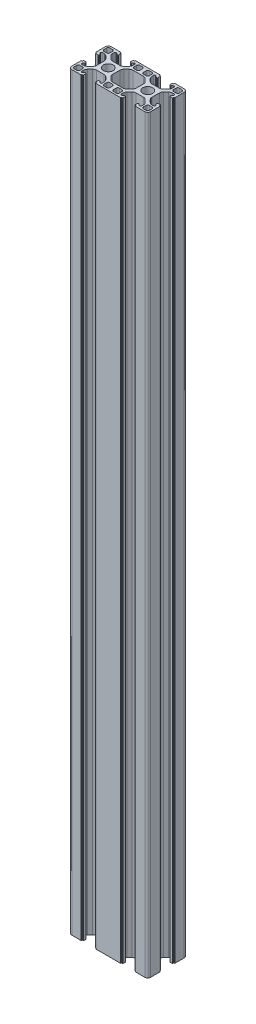
SolidWorks part; units mm, degrees
ref_plane "Спереди" through (0, 0, 0) normal (0, 0, 1) x (1, 0, 0)
ref_plane "Сверху" through (0, 0, 0) normal (0, 1, 0) x (1, 0, 0)
ref_plane "Справа" through (0, 0, 0) normal (1, 0, 0) x (0, 0, -1)
sketch "Эскиз1" plane through (0, 0, 0) normal (0, 1, 0) x (1, 0, 0)
  line L0 (-3.1522, 8.2837) -> (-1.6522, 6.7837) construction
  line L1 (18.3478, 9.7837) -> (15.3478, 6.7837) construction
  line L2 (-10.7522, 0.6837) -> (-0.7522, 10.6837) construction
  line L3 (9.2478, 4.6837) -> (11.1466, 4.6837)
  line L4 (9.2478, 0.6837) -> (19.2478, 10.6837) construction
  line L5 (16.8478, 8.2837) -> (15.3478, 9.7837) construction
  line L6 (12.5608, 5.2695) -> (13.862, 6.5707)
  line L7 (16.1478, 6.7837) -> (17.5478, 6.7837)
  line L8 (15.3478, 7.5837) -> (15.3478, 8.9837)
  line L9 (17.5478, 9.7837) -> (16.1478, 9.7837)
  line L10 (14.4478, 8.8837) -> (14.4478, 7.9849)
  line L11 (13.011, 8.757) -> (13.4914, 9.2373)
  line L12 (12.4478, 10.2328) -> (12.9478, 10.2328)
  line L13 (12.8343, 8.6837) -> (12.5478, 8.6837)
  line L14 (13.8449, 9.3837) -> (13.9478, 9.3837)
  line L15 (12.9478, 10.5337) -> (12.9478, 10.2328)
  line L16 (12.2978, 10.0828) -> (12.2978, 8.9337)
  line L17 (17.7478, 10.6837) -> (13.0978, 10.6837)
  line L18 (18.3478, 8.9837) -> (18.3478, 7.5837)
  line L19 (19.2478, 9.1837) -> (19.2478, 4.5337)
  line L20 (18.6469, 3.7337) -> (17.4978, 3.7337)
  line L21 (19.0978, 4.3837) -> (18.7969, 4.3837)
  line L22 (17.9478, 5.2808) -> (17.9478, 5.3837)
  line L23 (17.2478, 4.2702) -> (17.2478, 3.9837)
  line L24 (18.7969, 3.8837) -> (18.7969, 4.3837)
  line L25 (17.321, 4.447) -> (17.8014, 4.9273)
  line L26 (17.4478, 5.8837) -> (16.549, 5.8837)
  line L27 (13.8336, 3.9967) -> (15.1348, 5.2979)
  line L28 (13.2478, 0.6837) -> (13.2478, 2.5825)
  line L29 (13.2478, 0.6837) -> (13.2478, -1.2151)
  line L30 (13.8336, -2.6293) -> (15.1348, -3.9305)
  line L31 (15.3478, -6.2163) -> (15.3478, -7.6163)
  line L32 (16.1478, -5.4163) -> (17.5478, -5.4163)
  line L33 (18.3478, -7.6163) -> (18.3478, -6.2163)
  line L34 (17.4478, -4.5163) -> (16.549, -4.5163)
  line L35 (17.321, -3.0795) -> (17.8014, -3.5598)
  line L36 (18.7969, -2.5163) -> (18.7969, -3.0163)
  line L37 (17.2478, -2.9027) -> (17.2478, -2.6163)
  line L38 (17.9478, -3.9134) -> (17.9478, -4.0163)
  line L39 (19.0978, -3.0163) -> (18.7969, -3.0163)
  line L40 (18.6469, -2.3663) -> (17.4978, -2.3663)
  line L41 (19.2478, -7.8163) -> (19.2478, -3.1663)
  line L42 (17.5478, -8.4163) -> (16.1478, -8.4163)
  line L43 (17.7478, -9.3163) -> (13.0978, -9.3163)
  line L44 (12.2978, -8.7153) -> (12.2978, -7.5663)
  line L45 (12.9478, -9.1663) -> (12.9478, -8.8653)
  line L46 (13.8449, -8.0163) -> (13.9478, -8.0163)
  line L47 (12.8343, -7.3163) -> (12.5478, -7.3163)
  line L48 (12.4478, -8.8653) -> (12.9478, -8.8653)
  line L49 (13.011, -7.3895) -> (13.4914, -7.8698)
  line L50 (14.4478, -7.5163) -> (14.4478, -6.6175)
  line L51 (12.5608, -3.9021) -> (13.862, -5.2033)
  line L52 (9.2478, -3.3163) -> (11.1466, -3.3163)
  line L53 (18.3478, -8.4163) -> (15.3478, -5.4163) construction
  line L54 (9.2478, 0.6837) -> (19.2478, -9.3163) construction
  line L55 (16.8478, -6.9163) -> (18.3478, -5.4163) construction
  line L56 (9.2478, -3.3163) -> (7.349, -3.3163)
  line L57 (5.9348, -3.9021) -> (4.6336, -5.2033)
  line L58 (2.3478, -5.4163) -> (0.9478, -5.4163)
  line L59 (3.1478, -6.2163) -> (3.1478, -7.6163)
  line L60 (0.9478, -8.4163) -> (2.3478, -8.4163)
  line L61 (4.0478, -7.5163) -> (4.0478, -6.6175)
  line L62 (5.4846, -7.3895) -> (5.0043, -7.8698)
  line L63 (6.0478, -8.8653) -> (5.5478, -8.8653)
  line L64 (5.6614, -7.3163) -> (5.9478, -7.3163)
  line L65 (4.6507, -8.0163) -> (4.5478, -8.0163)
  line L66 (5.5478, -9.1663) -> (5.5478, -8.8653)
  line L67 (6.1978, -8.7153) -> (6.1978, -7.5663)
  line L68 (0.7478, -9.3163) -> (5.3978, -9.3163)
  line L69 (0.1478, -7.6163) -> (0.1478, -6.2163)
  line L70 (1.0478, -4.5163) -> (1.9466, -4.5163)
  line L71 (4.662, -2.6293) -> (3.3608, -3.9305)
  line L72 (5.2478, 0.6837) -> (5.2478, -1.2151)
  line L73 (-1.6522, 9.7837) -> (-4.6522, 6.7837) construction
  line L74 (0.1478, -8.4163) -> (3.1478, -5.4163) construction
  line L75 (-3.1522, -6.9163) -> (-4.6522, -8.4163) construction
  line L76 (9.2478, 0.6837) -> (-0.7522, -9.3163) construction
  line L77 (1.6478, -6.9163) -> (3.1478, -8.4163) construction
  line L78 (5.2478, 0.6837) -> (5.2478, 2.5825)
  line L79 (4.662, 3.9967) -> (3.3608, 5.2979)
  line L80 (3.1478, 7.5837) -> (3.1478, 8.9837)
  line L81 (2.3478, 6.7837) -> (0.9478, 6.7837)
  line L82 (0.1478, 8.9837) -> (0.1478, 7.5837)
  line L83 (1.0478, 5.8837) -> (1.9466, 5.8837)
  line L84 (0.9478, 9.7837) -> (2.3478, 9.7837)
  line L85 (0.7478, 10.6837) -> (5.3978, 10.6837)
  line L86 (6.1978, 10.0828) -> (6.1978, 8.9337)
  line L87 (5.5478, 10.5337) -> (5.5478, 10.2328)
  line L88 (4.6507, 9.3837) -> (4.5478, 9.3837)
  line L89 (5.6614, 8.6837) -> (5.9478, 8.6837)
  line L90 (6.0478, 10.2328) -> (5.5478, 10.2328)
  line L91 (5.4846, 8.757) -> (5.0043, 9.2373)
  line L92 (4.0478, 8.8837) -> (4.0478, 7.9849)
  line L93 (5.9348, 5.2695) -> (4.6336, 6.5707)
  line L94 (9.2478, 4.6837) -> (7.349, 4.6837)
  line L95 (-2.5162, 0.6837) -> (20.7522, 0.6837) construction
  line L96 (0.1478, 9.7837) -> (3.1478, 6.7837) construction
  line L97 (9.2478, -11.4027) -> (9.2478, 11.4027) construction
  line L98 (9.2478, 0.6837) -> (-0.7522, 10.6837) construction
  line L99 (1.6478, 8.2837) -> (0.1478, 6.7837) construction
  line L100 (-10.7522, 0.6837) -> (-0.7522, -9.3163) construction
  line L101 (-1.6522, -8.4163) -> (-4.6522, -5.4163) construction
  line L102 (-18.3522, -6.9163) -> (-19.8522, -5.4163) construction
  line L103 (-10.7522, 0.6837) -> (-20.7522, -9.3163) construction
  line L104 (-19.8522, -8.4163) -> (-16.8522, -5.4163) construction
  line L105 (-18.3522, 8.2837) -> (-16.8522, 9.7837) construction
  line L106 (-10.7522, 0.6837) -> (-20.7522, 10.6837) construction
  line L107 (-19.8522, 9.7837) -> (-16.8522, 6.7837) construction
  line L108 (-10.7522, 4.6837) -> (-8.8534, 4.6837)
  line L109 (-7.4392, 5.2695) -> (-6.138, 6.5707)
  line L110 (-5.5522, 8.8837) -> (-5.5522, 7.9849)
  line L111 (-6.989, 8.757) -> (-6.5086, 9.2373)
  line L112 (-7.5522, 10.2328) -> (-7.0522, 10.2328)
  line L113 (-7.1657, 8.6837) -> (-7.4522, 8.6837)
  line L114 (-6.1551, 9.3837) -> (-6.0522, 9.3837)
  line L115 (-7.0522, 10.5337) -> (-7.0522, 10.2328)
  line L116 (-7.7022, 10.0828) -> (-7.7022, 8.9337)
  line L117 (-2.2522, 10.6837) -> (-6.9022, 10.6837)
  line L118 (-2.4522, 9.7837) -> (-3.8522, 9.7837)
  line L119 (-2.5522, 5.8837) -> (-3.451, 5.8837)
  line L120 (-1.6522, 8.9837) -> (-1.6522, 7.5837)
  line L121 (-3.8522, 6.7837) -> (-2.4522, 6.7837)
  line L122 (-4.6522, 7.5837) -> (-4.6522, 8.9837)
  line L123 (-6.1664, 3.9967) -> (-4.8652, 5.2979)
  line L124 (-6.7522, 0.6837) -> (-6.7522, 2.5825)
  line L125 (-6.7522, 0.6837) -> (-6.7522, -1.2151)
  line L126 (-6.1664, -2.6293) -> (-4.8652, -3.9305)
  line L127 (-2.5522, -4.5163) -> (-3.451, -4.5163)
  line L128 (-1.6522, -7.6163) -> (-1.6522, -6.2163)
  line L129 (-2.2522, -9.3163) -> (-6.9022, -9.3163)
  line L130 (-7.7022, -8.7153) -> (-7.7022, -7.5663)
  line L131 (-7.0522, -9.1663) -> (-7.0522, -8.8653)
  line L132 (-6.1551, -8.0163) -> (-6.0522, -8.0163)
  line L133 (-7.1657, -7.3163) -> (-7.4522, -7.3163)
  line L134 (-7.5522, -8.8653) -> (-7.0522, -8.8653)
  line L135 (-6.989, -7.3895) -> (-6.5086, -7.8698)
  line L136 (-5.5522, -7.5163) -> (-5.5522, -6.6175)
  line L137 (-2.4522, -8.4163) -> (-3.8522, -8.4163)
  line L138 (-4.6522, -6.2163) -> (-4.6522, -7.6163)
  line L139 (-3.8522, -5.4163) -> (-2.4522, -5.4163)
  line L140 (-7.4392, -3.9021) -> (-6.138, -5.2033)
  line L141 (-10.7522, -3.3163) -> (-8.8534, -3.3163)
  line L142 (-10.7522, -3.3163) -> (-12.651, -3.3163)
  line L143 (-14.0652, -3.9021) -> (-15.3664, -5.2033)
  line L144 (-15.9522, -7.5163) -> (-15.9522, -6.6175)
  line L145 (-14.5154, -7.3895) -> (-14.9957, -7.8698)
  line L146 (-13.9522, -8.8653) -> (-14.4522, -8.8653)
  line L147 (-14.3386, -7.3163) -> (-14.0522, -7.3163)
  line L148 (-15.3493, -8.0163) -> (-15.4522, -8.0163)
  line L149 (-14.4522, -9.1663) -> (-14.4522, -8.8653)
  line L150 (-13.8022, -8.7153) -> (-13.8022, -7.5663)
  line L151 (-19.2522, -9.3163) -> (-14.6022, -9.3163)
  line L152 (-19.0522, -8.4163) -> (-17.6522, -8.4163)
  line L153 (-20.7522, -7.8163) -> (-20.7522, -3.1663)
  line L154 (-20.1512, -2.3663) -> (-19.0022, -2.3663)
  line L155 (-20.6022, -3.0163) -> (-20.3012, -3.0163)
  line L156 (-19.4522, -3.9134) -> (-19.4522, -4.0163)
  line L157 (-18.7522, -2.9027) -> (-18.7522, -2.6163)
  line L158 (-20.3012, -2.5163) -> (-20.3012, -3.0163)
  line L159 (-18.8254, -3.0795) -> (-19.3057, -3.5598)
  line L160 (-18.9522, -4.5163) -> (-18.0534, -4.5163)
  line L161 (-19.8522, -7.6163) -> (-19.8522, -6.2163)
  line L162 (-17.6522, -5.4163) -> (-19.0522, -5.4163)
  line L163 (-16.8522, -6.2163) -> (-16.8522, -7.6163)
  line L164 (-15.338, -2.6293) -> (-16.6392, -3.9305)
  line L165 (-14.7522, 0.6837) -> (-14.7522, -1.2151)
  line L166 (-14.7522, 0.6837) -> (-14.7522, 2.5825)
  line L167 (-15.338, 3.9967) -> (-16.6392, 5.2979)
  line L168 (-18.9522, 5.8837) -> (-18.0534, 5.8837)
  line L169 (-18.8254, 4.447) -> (-19.3057, 4.9273)
  line L170 (-20.3012, 3.8837) -> (-20.3012, 4.3837)
  line L171 (-18.7522, 4.2702) -> (-18.7522, 3.9837)
  line L172 (-19.4522, 5.2808) -> (-19.4522, 5.3837)
  line L173 (-20.6022, 4.3837) -> (-20.3012, 4.3837)
  line L174 (-20.1512, 3.7337) -> (-19.0022, 3.7337)
  line L175 (-20.7522, 9.1837) -> (-20.7522, 4.5337)
  line L176 (-19.8522, 8.9837) -> (-19.8522, 7.5837)
  line L177 (-19.2522, 10.6837) -> (-14.6022, 10.6837)
  line L178 (-13.8022, 10.0828) -> (-13.8022, 8.9337)
  line L179 (-14.4522, 10.5337) -> (-14.4522, 10.2328)
  line L180 (-15.3493, 9.3837) -> (-15.4522, 9.3837)
  line L181 (-14.3386, 8.6837) -> (-14.0522, 8.6837)
  line L182 (-13.9522, 10.2328) -> (-14.4522, 10.2328)
  line L183 (-14.5154, 8.757) -> (-14.9957, 9.2373)
  line L184 (-15.9522, 8.8837) -> (-15.9522, 7.9849)
  line L185 (-19.0522, 9.7837) -> (-17.6522, 9.7837)
  line L186 (-16.8522, 7.5837) -> (-16.8522, 8.9837)
  line L187 (-17.6522, 6.7837) -> (-19.0522, 6.7837)
  line L188 (-14.0652, 5.2695) -> (-15.3664, 6.5707)
  line L189 (-10.7522, 4.6837) -> (-12.651, 4.6837)
  line L190 (-2.2522, -9.3163) -> (0.7478, -9.3163)
  line L191 (-2.5522, -4.5163) -> (1.0478, -4.5163)
  line L192 (-2.5522, 5.8837) -> (1.0478, 5.8837)
  line L193 (-2.2522, 10.6837) -> (0.7478, 10.6837)
  arc A0 (18.3478, 8.9837) -> (17.5478, 9.7837) centre (17.5478, 8.9837) ccw
  arc A1 (16.1478, 9.7837) -> (15.3478, 8.9837) centre (16.1478, 8.9837) ccw
  arc A2 (16.1478, 6.7837) -> (15.3478, 7.5837) centre (16.1478, 7.5837) cw
  arc A3 (17.7478, 10.6837) -> (19.2478, 9.1837) centre (17.7478, 9.1837) cw
  arc A4 (12.4478, 10.2328) -> (12.2978, 10.0828) centre (12.4478, 10.0828) ccw
  arc A5 (13.0978, 10.6837) -> (12.9478, 10.5337) centre (13.0978, 10.5337) ccw
  arc A6 (12.8343, 8.6837) -> (13.011, 8.757) centre (12.8343, 8.9337) ccw
  arc A7 (12.5478, 8.6837) -> (12.2978, 8.9337) centre (12.5478, 8.9337) cw
  arc A8 (13.4914, 9.2373) -> (13.8449, 9.3837) centre (13.8449, 8.8837) cw
  arc A9 (13.9478, 9.3837) -> (14.4478, 8.8837) centre (13.9478, 8.8837) cw
  arc A10 (11.7478, 0.6837) -> (9.2478, 3.1837) centre (9.2478, 0.6837) ccw
  arc A11 (11.1466, 4.6837) -> (12.5608, 5.2695) centre (11.1466, 6.6837) ccw
  arc A12 (14.4478, 7.9849) -> (13.862, 6.5707) centre (12.4478, 7.9849) cw
  arc A13 (18.3478, 7.5837) -> (17.5478, 6.7837) centre (17.5478, 7.5837) cw
  arc A14 (17.9478, 5.3837) -> (17.4478, 5.8837) centre (17.4478, 5.3837) ccw
  arc A15 (17.8014, 4.9273) -> (17.9478, 5.2808) centre (17.4478, 5.2808) ccw
  arc A16 (17.2478, 3.9837) -> (17.4978, 3.7337) centre (17.4978, 3.9837) ccw
  arc A17 (17.2478, 4.2702) -> (17.321, 4.447) centre (17.4978, 4.2702) cw
  arc A18 (19.2478, 4.5337) -> (19.0978, 4.3837) centre (19.0978, 4.5337) cw
  arc A19 (18.7969, 3.8837) -> (18.6469, 3.7337) centre (18.6469, 3.8837) cw
  arc A20 (16.549, 5.8837) -> (15.1348, 5.2979) centre (16.549, 3.8837) ccw
  arc A21 (13.2478, 2.5825) -> (13.8336, 3.9967) centre (15.2478, 2.5825) cw
  arc A22 (17.5478, -8.4163) -> (18.3478, -7.6163) centre (17.5478, -7.6163) ccw
  arc A23 (18.3478, -6.2163) -> (17.5478, -5.4163) centre (17.5478, -6.2163) ccw
  arc A24 (15.3478, -6.2163) -> (16.1478, -5.4163) centre (16.1478, -6.2163) cw
  arc A25 (19.2478, -7.8163) -> (17.7478, -9.3163) centre (17.7478, -7.8163) cw
  arc A26 (18.7969, -2.5163) -> (18.6469, -2.3663) centre (18.6469, -2.5163) ccw
  arc A27 (19.2478, -3.1663) -> (19.0978, -3.0163) centre (19.0978, -3.1663) ccw
  arc A28 (17.2478, -2.9027) -> (17.321, -3.0795) centre (17.4978, -2.9027) ccw
  arc A29 (17.2478, -2.6163) -> (17.4978, -2.3663) centre (17.4978, -2.6163) cw
  arc A30 (17.8014, -3.5598) -> (17.9478, -3.9134) centre (17.4478, -3.9134) cw
  arc A31 (17.9478, -4.0163) -> (17.4478, -4.5163) centre (17.4478, -4.0163) cw
  arc A32 (9.2478, -1.8163) -> (11.7478, 0.6837) centre (9.2478, 0.6837) ccw
  arc A33 (13.2478, -1.2151) -> (13.8336, -2.6293) centre (15.2478, -1.2151) ccw
  arc A34 (16.549, -4.5163) -> (15.1348, -3.9305) centre (16.549, -2.5163) cw
  arc A35 (16.1478, -8.4163) -> (15.3478, -7.6163) centre (16.1478, -7.6163) cw
  arc A36 (13.9478, -8.0163) -> (14.4478, -7.5163) centre (13.9478, -7.5163) ccw
  arc A37 (13.4914, -7.8698) -> (13.8449, -8.0163) centre (13.8449, -7.5163) ccw
  arc A38 (12.5478, -7.3163) -> (12.2978, -7.5663) centre (12.5478, -7.5663) ccw
  arc A39 (12.8343, -7.3163) -> (13.011, -7.3895) centre (12.8343, -7.5663) cw
  arc A40 (13.0978, -9.3163) -> (12.9478, -9.1663) centre (13.0978, -9.1663) cw
  arc A41 (12.4478, -8.8653) -> (12.2978, -8.7153) centre (12.4478, -8.7153) cw
  arc A42 (14.4478, -6.6175) -> (13.862, -5.2033) centre (12.4478, -6.6175) ccw
  arc A43 (11.1466, -3.3163) -> (12.5608, -3.9021) centre (11.1466, -5.3163) cw
  arc A44 (0.1478, -7.6163) -> (0.9478, -8.4163) centre (0.9478, -7.6163) ccw
  arc A45 (2.3478, -8.4163) -> (3.1478, -7.6163) centre (2.3478, -7.6163) ccw
  arc A46 (2.3478, -5.4163) -> (3.1478, -6.2163) centre (2.3478, -6.2163) cw
  arc A47 (6.0478, -8.8653) -> (6.1978, -8.7153) centre (6.0478, -8.7153) ccw
  arc A48 (5.3978, -9.3163) -> (5.5478, -9.1663) centre (5.3978, -9.1663) ccw
  arc A49 (5.6614, -7.3163) -> (5.4846, -7.3895) centre (5.6614, -7.5663) ccw
  arc A50 (5.9478, -7.3163) -> (6.1978, -7.5663) centre (5.9478, -7.5663) cw
  arc A51 (5.0043, -7.8698) -> (4.6507, -8.0163) centre (4.6507, -7.5163) cw
  arc A52 (4.5478, -8.0163) -> (4.0478, -7.5163) centre (4.5478, -7.5163) cw
  arc A53 (6.7478, 0.6837) -> (9.2478, -1.8163) centre (9.2478, 0.6837) ccw
  arc A54 (7.349, -3.3163) -> (5.9348, -3.9021) centre (7.349, -5.3163) ccw
  arc A55 (4.0478, -6.6175) -> (4.6336, -5.2033) centre (6.0478, -6.6175) cw
  arc A56 (0.1478, -6.2163) -> (0.9478, -5.4163) centre (0.9478, -6.2163) cw
  arc A57 (1.9466, -4.5163) -> (3.3608, -3.9305) centre (1.9466, -2.5163) ccw
  arc A58 (5.2478, -1.2151) -> (4.662, -2.6293) centre (3.2478, -1.2151) cw
  arc A59 (0.9478, 9.7837) -> (0.1478, 8.9837) centre (0.9478, 8.9837) ccw
  arc A60 (0.1478, 7.5837) -> (0.9478, 6.7837) centre (0.9478, 7.5837) ccw
  arc A61 (3.1478, 7.5837) -> (2.3478, 6.7837) centre (2.3478, 7.5837) cw
  arc A62 (9.2478, 3.1837) -> (6.7478, 0.6837) centre (9.2478, 0.6837) ccw
  arc A63 (5.2478, 2.5825) -> (4.662, 3.9967) centre (3.2478, 2.5825) ccw
  arc A64 (1.9466, 5.8837) -> (3.3608, 5.2979) centre (1.9466, 3.8837) cw
  arc A65 (2.3478, 9.7837) -> (3.1478, 8.9837) centre (2.3478, 8.9837) cw
  arc A66 (4.5478, 9.3837) -> (4.0478, 8.8837) centre (4.5478, 8.8837) ccw
  arc A67 (5.0043, 9.2373) -> (4.6507, 9.3837) centre (4.6507, 8.8837) ccw
  arc A68 (5.9478, 8.6837) -> (6.1978, 8.9337) centre (5.9478, 8.9337) ccw
  arc A69 (5.6614, 8.6837) -> (5.4846, 8.757) centre (5.6614, 8.9337) cw
  arc A70 (5.3978, 10.6837) -> (5.5478, 10.5337) centre (5.3978, 10.5337) cw
  arc A71 (6.0478, 10.2328) -> (6.1978, 10.0828) centre (6.0478, 10.0828) cw
  arc A72 (4.0478, 7.9849) -> (4.6336, 6.5707) centre (6.0478, 7.9849) ccw
  arc A73 (7.349, 4.6837) -> (5.9348, 5.2695) centre (7.349, 6.6837) cw
  arc A74 (-8.8534, 4.6837) -> (-7.4392, 5.2695) centre (-8.8534, 6.6837) ccw
  arc A75 (-5.5522, 7.9849) -> (-6.138, 6.5707) centre (-7.5522, 7.9849) cw
  arc A76 (-7.5522, 10.2328) -> (-7.7022, 10.0828) centre (-7.5522, 10.0828) ccw
  arc A77 (-6.9022, 10.6837) -> (-7.0522, 10.5337) centre (-6.9022, 10.5337) ccw
  arc A78 (-7.1657, 8.6837) -> (-6.989, 8.757) centre (-7.1657, 8.9337) ccw
  arc A79 (-7.4522, 8.6837) -> (-7.7022, 8.9337) centre (-7.4522, 8.9337) cw
  arc A80 (-6.5086, 9.2373) -> (-6.1551, 9.3837) centre (-6.1551, 8.8837) cw
  arc A81 (-6.0522, 9.3837) -> (-5.5522, 8.8837) centre (-6.0522, 8.8837) cw
  arc A82 (-3.8522, 9.7837) -> (-4.6522, 8.9837) centre (-3.8522, 8.9837) ccw
  arc A83 (-3.451, 5.8837) -> (-4.8652, 5.2979) centre (-3.451, 3.8837) ccw
  arc A84 (-6.7522, 2.5825) -> (-6.1664, 3.9967) centre (-4.7522, 2.5825) cw
  arc A85 (-10.7522, 3.1837) -> (-8.2522, 0.6837) centre (-10.7522, 0.6837) cw
  arc A86 (-4.6522, 7.5837) -> (-3.8522, 6.7837) centre (-3.8522, 7.5837) ccw
  arc A87 (-1.6522, 7.5837) -> (-2.4522, 6.7837) centre (-2.4522, 7.5837) cw
  arc A88 (-2.4522, 9.7837) -> (-1.6522, 8.9837) centre (-2.4522, 8.9837) cw
  arc A89 (-6.7522, -1.2151) -> (-6.1664, -2.6293) centre (-4.7522, -1.2151) ccw
  arc A90 (-3.451, -4.5163) -> (-4.8652, -3.9305) centre (-3.451, -2.5163) cw
  arc A91 (-1.6522, -6.2163) -> (-2.4522, -5.4163) centre (-2.4522, -6.2163) ccw
  arc A92 (-5.5522, -6.6175) -> (-6.138, -5.2033) centre (-7.5522, -6.6175) ccw
  arc A93 (-8.8534, -3.3163) -> (-7.4392, -3.9021) centre (-8.8534, -5.3163) cw
  arc A94 (-8.2522, 0.6837) -> (-10.7522, -1.8163) centre (-10.7522, 0.6837) cw
  arc A95 (-6.0522, -8.0163) -> (-5.5522, -7.5163) centre (-6.0522, -7.5163) ccw
  arc A96 (-6.5086, -7.8698) -> (-6.1551, -8.0163) centre (-6.1551, -7.5163) ccw
  arc A97 (-7.4522, -7.3163) -> (-7.7022, -7.5663) centre (-7.4522, -7.5663) ccw
  arc A98 (-7.1657, -7.3163) -> (-6.989, -7.3895) centre (-7.1657, -7.5663) cw
  arc A99 (-6.9022, -9.3163) -> (-7.0522, -9.1663) centre (-6.9022, -9.1663) cw
  arc A100 (-7.5522, -8.8653) -> (-7.7022, -8.7153) centre (-7.5522, -8.7153) cw
  arc A101 (-3.8522, -5.4163) -> (-4.6522, -6.2163) centre (-3.8522, -6.2163) ccw
  arc A102 (-3.8522, -8.4163) -> (-4.6522, -7.6163) centre (-3.8522, -7.6163) cw
  arc A103 (-1.6522, -7.6163) -> (-2.4522, -8.4163) centre (-2.4522, -7.6163) cw
  arc A104 (-12.651, -3.3163) -> (-14.0652, -3.9021) centre (-12.651, -5.3163) ccw
  arc A105 (-15.9522, -6.6175) -> (-15.3664, -5.2033) centre (-13.9522, -6.6175) cw
  arc A106 (-13.9522, -8.8653) -> (-13.8022, -8.7153) centre (-13.9522, -8.7153) ccw
  arc A107 (-14.6022, -9.3163) -> (-14.4522, -9.1663) centre (-14.6022, -9.1663) ccw
  arc A108 (-14.3386, -7.3163) -> (-14.5154, -7.3895) centre (-14.3386, -7.5663) ccw
  arc A109 (-14.0522, -7.3163) -> (-13.8022, -7.5663) centre (-14.0522, -7.5663) cw
  arc A110 (-14.9957, -7.8698) -> (-15.3493, -8.0163) centre (-15.3493, -7.5163) cw
  arc A111 (-15.4522, -8.0163) -> (-15.9522, -7.5163) centre (-15.4522, -7.5163) cw
  arc A112 (-17.6522, -8.4163) -> (-16.8522, -7.6163) centre (-17.6522, -7.6163) ccw
  arc A113 (-18.0534, -4.5163) -> (-16.6392, -3.9305) centre (-18.0534, -2.5163) ccw
  arc A114 (-14.7522, -1.2151) -> (-15.338, -2.6293) centre (-16.7522, -1.2151) cw
  arc A115 (-10.7522, -1.8163) -> (-13.2522, 0.6837) centre (-10.7522, 0.6837) cw
  arc A116 (-19.4522, -4.0163) -> (-18.9522, -4.5163) centre (-18.9522, -4.0163) ccw
  arc A117 (-19.3057, -3.5598) -> (-19.4522, -3.9134) centre (-18.9522, -3.9134) ccw
  arc A118 (-18.7522, -2.6163) -> (-19.0022, -2.3663) centre (-19.0022, -2.6163) ccw
  arc A119 (-18.7522, -2.9027) -> (-18.8254, -3.0795) centre (-19.0022, -2.9027) cw
  arc A120 (-20.7522, -3.1663) -> (-20.6022, -3.0163) centre (-20.6022, -3.1663) cw
  arc A121 (-20.3012, -2.5163) -> (-20.1512, -2.3663) centre (-20.1512, -2.5163) cw
  arc A122 (-20.7522, -7.8163) -> (-19.2522, -9.3163) centre (-19.2522, -7.8163) ccw
  arc A123 (-16.8522, -6.2163) -> (-17.6522, -5.4163) centre (-17.6522, -6.2163) ccw
  arc A124 (-19.8522, -6.2163) -> (-19.0522, -5.4163) centre (-19.0522, -6.2163) cw
  arc A125 (-19.0522, -8.4163) -> (-19.8522, -7.6163) centre (-19.0522, -7.6163) cw
  arc A126 (-14.7522, 2.5825) -> (-15.338, 3.9967) centre (-16.7522, 2.5825) ccw
  arc A127 (-18.0534, 5.8837) -> (-16.6392, 5.2979) centre (-18.0534, 3.8837) cw
  arc A128 (-20.3012, 3.8837) -> (-20.1512, 3.7337) centre (-20.1512, 3.8837) ccw
  arc A129 (-20.7522, 4.5337) -> (-20.6022, 4.3837) centre (-20.6022, 4.5337) ccw
  arc A130 (-18.7522, 4.2702) -> (-18.8254, 4.447) centre (-19.0022, 4.2702) ccw
  arc A131 (-18.7522, 3.9837) -> (-19.0022, 3.7337) centre (-19.0022, 3.9837) cw
  arc A132 (-19.3057, 4.9273) -> (-19.4522, 5.2808) centre (-18.9522, 5.2808) cw
  arc A133 (-19.4522, 5.3837) -> (-18.9522, 5.8837) centre (-18.9522, 5.3837) cw
  arc A134 (-19.8522, 7.5837) -> (-19.0522, 6.7837) centre (-19.0522, 7.5837) ccw
  arc A135 (-15.9522, 7.9849) -> (-15.3664, 6.5707) centre (-13.9522, 7.9849) ccw
  arc A136 (-12.651, 4.6837) -> (-14.0652, 5.2695) centre (-12.651, 6.6837) cw
  arc A137 (-13.2522, 0.6837) -> (-10.7522, 3.1837) centre (-10.7522, 0.6837) cw
  arc A138 (-15.4522, 9.3837) -> (-15.9522, 8.8837) centre (-15.4522, 8.8837) ccw
  arc A139 (-14.9957, 9.2373) -> (-15.3493, 9.3837) centre (-15.3493, 8.8837) ccw
  arc A140 (-14.0522, 8.6837) -> (-13.8022, 8.9337) centre (-14.0522, 8.9337) ccw
  arc A141 (-14.3386, 8.6837) -> (-14.5154, 8.757) centre (-14.3386, 8.9337) cw
  arc A142 (-14.6022, 10.6837) -> (-14.4522, 10.5337) centre (-14.6022, 10.5337) cw
  arc A143 (-13.9522, 10.2328) -> (-13.8022, 10.0828) centre (-13.9522, 10.0828) cw
  arc A144 (-19.2522, 10.6837) -> (-20.7522, 9.1837) centre (-19.2522, 9.1837) ccw
  arc A145 (-17.6522, 6.7837) -> (-16.8522, 7.5837) centre (-17.6522, 7.5837) ccw
  arc A146 (-17.6522, 9.7837) -> (-16.8522, 8.9837) centre (-17.6522, 8.9837) cw
  arc A147 (-19.8522, 8.9837) -> (-19.0522, 9.7837) centre (-19.0522, 8.9837) cw
  point P0 (9.2478, 0.6837)
  point P12 (9.2478, 0.6837)
  point P45 (17.9478, 4.3837)
  point P104 (12.9478, -8.0163)
  point P155 (12.9478, 9.3837)
  point P163 (17.9478, -3.0163)
  point P164 (9.2478, -3.2405)
  point P166 (9.2478, 0.6837)
  point P224 (5.5478, -8.0163)
  point P225 (5.3236, 0.6837)
  point P227 (9.2478, 0.6837)
  point P267 (5.5478, 9.3837)
  point P272 (13.1721, 0.6837)
  point P288 (9.2478, 4.608)
  point P290 (9.2478, 0.6837)
  point P515 (-10.7522, 4.608)
  point P516 (-14.6764, 0.6837)
  point P517 (-7.0522, 9.3837)
  point P518 (-6.8279, 0.6837)
  point P519 (-7.0522, -8.0163)
  point P520 (-10.7522, -3.2405)
  point P521 (-19.4522, -3.0163)
  point P522 (-14.4522, 9.3837)
  point P523 (-14.4522, -8.0163)
  point P524 (-19.4522, 4.3837)
extrude "Бобышка-Вытянуть1" add sketch "Эскиз1" along normal blind 380
